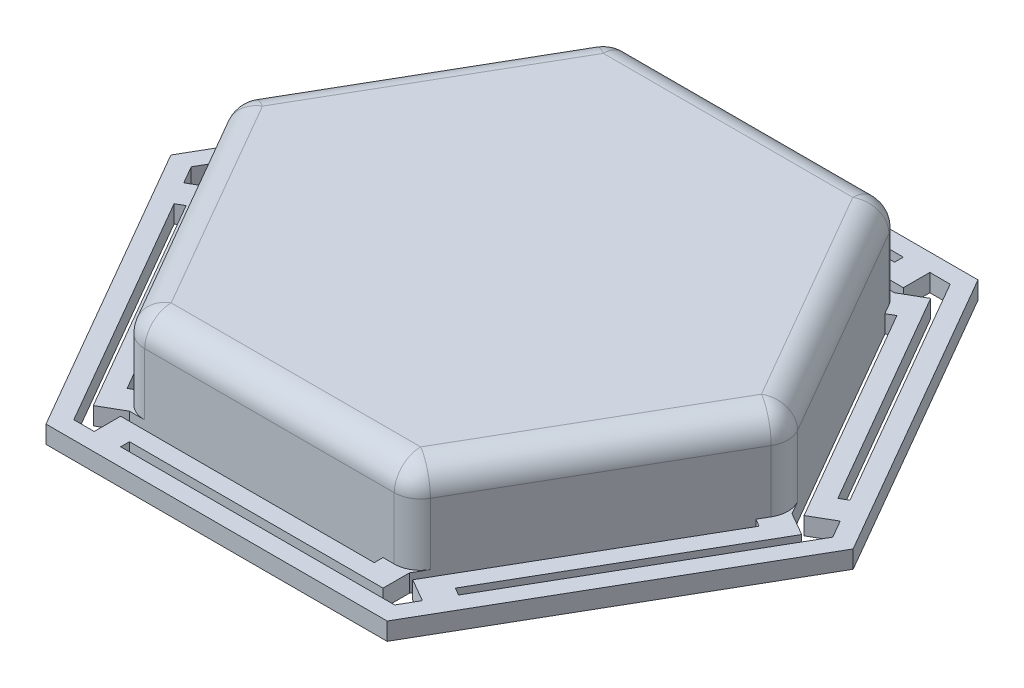
SolidWorks part; units mm, degrees
material "ABS"
ref_plane "Front Plane" through (0, 0, 0) normal (0, 0, 1) x (1, 0, 0)
ref_plane "Top Plane" through (0, 0, 0) normal (0, 1, 0) x (1, 0, 0)
ref_plane "Right Plane" through (0, 0, 0) normal (1, 0, 0) x (0, 0, -1)
sketch "Sketch1" plane through (0, 0, 0) normal (0, 1, 0) x (1, 0, 0)
  line L0 (-23.0969, 40.005) -> (-24.5634, 37.465)
  line L1 (20.164, -34.925) -> (38.4229, -3.2996)
  line L2 (40.3279, 0) -> (22.069, 31.6254)
  line L3 (20.164, 34.925) -> (-16.354, 34.925)
  line L4 (-20.164, 34.925) -> (-38.4229, 3.2996)
  line L5 (-40.3279, 0) -> (-22.069, -31.6254)
  line L6 (-20.164, -34.925) -> (16.354, -34.925)
  line L7 (49.1267, 0) -> (24.5634, 42.545)
  line L8 (24.5634, 42.545) -> (-24.5634, 42.545)
  line L9 (-24.5634, 42.545) -> (-49.1267, 0)
  line L10 (-49.1267, 0) -> (-24.5634, -42.545)
  line L11 (-24.5634, -42.545) -> (24.5634, -42.545)
  line L12 (24.5634, -42.545) -> (49.1267, 0)
  line L16 (-16.354, 34.925) -> (-16.354, 36.195)
  line L17 (-16.354, 36.195) -> (20.164, 36.195)
  line L19 (-20.164, 38.735) -> (16.354, 38.735)
  line L24 (16.354, 38.735) -> (16.354, 40.005)
  line L33 (-46.1938, 0) -> (-44.7273, -2.54)
  line L34 (-23.0969, -40.005) -> (-20.164, -40.005)
  line L35 (23.0969, -40.005) -> (24.5634, -37.465)
  line L36 (46.1938, 0) -> (44.7273, 2.54)
  line L37 (23.0969, 40.005) -> (20.164, 40.005)
  line L39 (16.354, 40.005) -> (-23.0969, 40.005)
  line L40 (23.0969, 40.005) -> (-23.0969, 40.005) construction
  line L41 (-20.164, 38.735) -> (-20.164, 34.925)
  line L42 (20.164, 40.005) -> (20.164, 36.195)
  line L43 (23.4635, 36.83) -> (20.164, 34.925)
  line L44 (22.069, 31.6254) -> (23.1688, 32.2604)
  line L45 (23.1688, 32.2604) -> (41.4278, 0.635)
  line L46 (23.4635, 36.83) -> (41.7225, 5.2046)
  line L47 (44.7273, 2.54) -> (41.4278, 0.635)
  line L48 (41.7225, 5.2046) -> (42.8223, 5.8396)
  line L49 (43.6275, -1.905) -> (40.3279, 0)
  line L50 (38.4229, -3.2996) -> (39.5228, -3.9346)
  line L51 (39.5228, -3.9346) -> (21.2638, -35.56)
  line L52 (43.6275, -1.905) -> (25.3685, -33.5304)
  line L53 (24.5634, -37.465) -> (21.2638, -35.56)
  line L54 (25.3685, -33.5304) -> (26.4684, -34.1654)
  line L55 (20.164, -38.735) -> (20.164, -34.925)
  line L56 (16.354, -34.925) -> (16.354, -36.195)
  line L57 (16.354, -36.195) -> (-20.164, -36.195)
  line L58 (20.164, -38.735) -> (-16.354, -38.735)
  line L59 (-20.164, -40.005) -> (-20.164, -36.195)
  line L60 (-16.354, -38.735) -> (-16.354, -40.005)
  line L61 (-23.4635, -36.83) -> (-20.164, -34.925)
  line L62 (-22.069, -31.6254) -> (-23.1688, -32.2604)
  line L63 (-23.1688, -32.2604) -> (-41.4278, -0.635)
  line L64 (-23.4635, -36.83) -> (-41.7225, -5.2046)
  line L65 (-44.7273, -2.54) -> (-41.4278, -0.635)
  line L66 (-41.7225, -5.2046) -> (-42.8223, -5.8396)
  line L67 (-43.6275, 1.905) -> (-40.3279, 0)
  line L68 (-38.4229, 3.2996) -> (-39.5228, 3.9346)
  line L69 (-39.5228, 3.9346) -> (-21.2638, 35.56)
  line L70 (-43.6275, 1.905) -> (-25.3685, 33.5304)
  line L71 (-24.5634, 37.465) -> (-21.2638, 35.56)
  line L72 (-25.3685, 33.5304) -> (-26.4684, 34.1654)
  line L73 (-26.4684, 34.1654) -> (-46.1938, 0)
  line L74 (-23.0969, 40.005) -> (-46.1938, 0) construction
  line L75 (-42.8223, -5.8396) -> (-23.0969, -40.005)
  line L76 (-46.1938, 0) -> (-23.0969, -40.005) construction
  line L77 (-16.354, -40.005) -> (23.0969, -40.005)
  line L78 (-23.0969, -40.005) -> (23.0969, -40.005) construction
  line L79 (26.4684, -34.1654) -> (46.1938, 0)
  line L80 (23.0969, -40.005) -> (46.1938, 0) construction
  line L81 (42.8223, 5.8396) -> (23.0969, 40.005)
  line L82 (46.1938, 0) -> (23.0969, 40.005) construction
  circle A0 centre (0, 0) radius 34.925 construction
  circle A1 centre (0, 0) radius 42.545 construction
  point P72 (0, 0)
  dimension "D1" = 69.85
  dimension "D2" = 7.62
  dimension "D4" = 3.81
  dimension "D5" = 3.81
  dimension "D6" = 3.81
extrude "Boss-Extrude2" add sketch "Sketch1" along normal blind 2.54 contours L11 L12 L7 L8 L9 L10 L81 L48 L46 L43 L3 L16 L17 L42 L37 L79 L54 L52 L49 L2 L44 L45 L47 L36 L77 L60 L58 L55 L1 L50 L51 L53 L35 L75 L66 L64 L61 L6 L56 L57 L59 L34 L73 L72 L70 L67 | L4 L68 L69 L71 L0 L39 L24 L19 L41
sketch "Sketch2" plane through (0, 2.54, 0) normal (0, 1, 0) x (1, 0, 0)
  line L0 (20.164, 34.925) -> (-16.354, 34.925) construction
  line L1 (-20.164, 34.925) -> (-40.3279, 0)
  line L2 (-40.3279, 0) -> (-20.164, -34.925)
  line L3 (-20.164, -34.925) -> (20.164, -34.925)
  line L4 (20.164, -34.925) -> (40.3279, 0)
  line L5 (40.3279, 0) -> (20.164, 34.925)
  line L6 (20.164, 34.925) -> (-20.164, 34.925)
  circle A0 centre (0, 0) radius 34.925 construction
extrude "Boss-Extrude3" add sketch "Sketch2" along normal blind 12.7
sketch "Sketch3" plane through (0, 0, 0) normal (0, -1, 0) x (1, 0, 0)
  line L0 (20.164, -34.925) -> (-16.354, -34.925) construction
  line L1 (17.231, -29.845) -> (34.462, 0)
  line L2 (34.462, 0) -> (17.231, 29.845)
  line L3 (17.231, 29.845) -> (-17.231, 29.845)
  line L4 (-17.231, 29.845) -> (-34.462, 0)
  line L5 (-34.462, 0) -> (-17.231, -29.845)
  line L6 (-17.231, -29.845) -> (17.231, -29.845)
  circle A0 centre (0, 0) radius 29.845 construction
  dimension "D1" = 5.08
extrude "Cut-Extrude1" cut sketch "Sketch3" against normal blind 13.97
fillet "Fillet1" radius 3.81 12 edges at (30.2459, 15.24, -17.4625) (30.2459, 15.24, 17.4625) (0, 15.24, 34.925) (-30.2459, 15.24, 17.4625) (-30.2459, 15.24, -17.4625) (0, 15.24, -34.925) (-20.164, 8.89, -34.925) (20.164, 8.89, -34.925) (40.3279, 8.89, 0) (20.164, 8.89, 34.925) (-20.164, 8.89, 34.925) (-40.3279, 8.89, 0)
